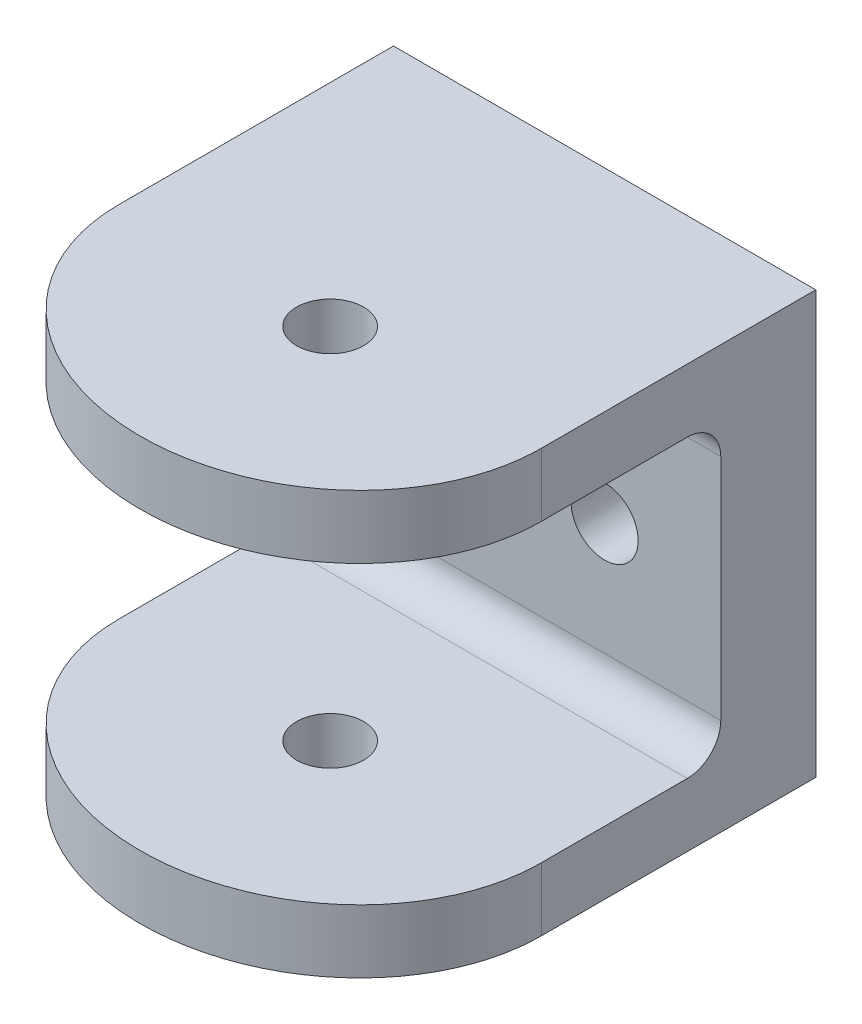
SolidWorks part; units mm, degrees
ref_plane "Front Plane" through (0, 0, 0) normal (0, 0, 1) x (1, 0, 0)
ref_plane "Top Plane" through (0, 0, 0) normal (0, 1, 0) x (1, 0, 0)
ref_plane "Right Plane" through (0, 0, 0) normal (1, 0, 0) x (0, 0, -1)
sketch "Sketch1" plane through (0, 0, 0) normal (0, 0, 1) x (1, 0, 0)
  line L0 (0, 0) -> (-9, 0) construction
  line L1 (-20, -20) -> (20, -20)
  line L2 (-20, -20) -> (-20, 20)
  line L3 (-20, 20) -> (20, 20)
  line L4 (20, -20) -> (20, 20)
  line L5 (-20, -20) -> (20, 20) construction
  line L6 (-20, 20) -> (20, -20) construction
  line L7 (0, 0) -> (9, 0) construction
  circle A0 centre (9, 0) radius 3.175
  circle A1 centre (-9, 0) radius 3.175
  point P0 (0, 0)
  dimension "D4" = 6.35
  dimension "D1" = 40
  dimension "D2" = 40
  dimension "D3" = 18
extrude "Boss-Extrude1" add sketch "Sketch1" along normal blind 9
sketch "Sketch2" plane through (0, 0, 9) normal (0, 0, 1) x (1, 0, 0)
  line L1 (-20, 20) -> (20, 20)
  line L2 (-20, 20) -> (-20, 14)
  line L3 (-20, 14) -> (20, 14)
  line L4 (20, -20) -> (20, 20)
  line L5 (20, 20) -> (-20, 20)
  line L6 (-20, 20) -> (-20, -20)
  line L7 (-20, -20) -> (20, -20)
  line L8 (20, -20) -> (20, 20) construction
  line L9 (20, 20) -> (-20, 20) construction
  line L10 (-20, 20) -> (-20, -20) construction
  line L11 (-20, -20) -> (20, -20) construction
  line L12 (20, 20) -> (20, 14)
  line L13 (20, -20) -> (-20, -20)
  line L14 (20, -20) -> (20, -14)
  line L15 (20, -14) -> (-20, -14)
  line L16 (-20, -20) -> (-20, -14)
  dimension "D2" = 6
  dimension "D3" = 6
  dimension "D1" = 0
extrude "Boss-Extrude2" add sketch "Sketch2" along normal blind 35
fillet "Fillet1" radius 3.175 2 edges at (0, 14, 9) (0, -14, 9)
sketch "Sketch3" plane through (0, 20, 0) normal (0, 1, 0) x (1, 0, 0)
  line L0 (20, -9) -> (-20, -9) construction
  line L1 (20, -9) -> (-20, -9) construction
  line L2 (20, -44) -> (20, 0) construction
  line L3 (20, -44) -> (20, -26)
  line L4 (-20, -44) -> (-20, 0) construction
  line L5 (20, -44) -> (-20, -44) construction
  line L6 (-20, -44) -> (-20, -26)
  line L7 (20, -44) -> (-20, -44)
  line L8 (20, 0) -> (-20, 0) construction
  circle A0 centre (0, -26) radius 3.175
  ellipse E0 centre (0, -26) end of major axis (20, -26) minor radius 18 (-20, -26) -> (20, -26) ccw
  point P4 (0, -9)
  point P7 (0, 0)
  point P18 (0, -44)
  point P19 (0, -44)
  line M6 (-20, 0) -> (-20, -44)
  line M7 (-20, -44) -> (20, -44)
  line M8 (20, -44) -> (20, 0)
  dimension "D1" = 6.35
  dimension "D2" = 26
  dimension "D3" = 20
  dimension "D4" = 18
extrude "Cut-Extrude1" cut sketch "Sketch3" against normal through all contours E0 M6 M7 | E0 L7 M8 | A0
ref_point "Point4"
ref_point "Point6"
ref_point "Point8"
ref_point "Point12"
sketch "Sketch4" plane through (0, 0, 0) normal (0, 1, 0) x (1, 0, 0)
  point P0 (0, -26)
  point P3 (0, 0)
  point P4 (0, 0)
